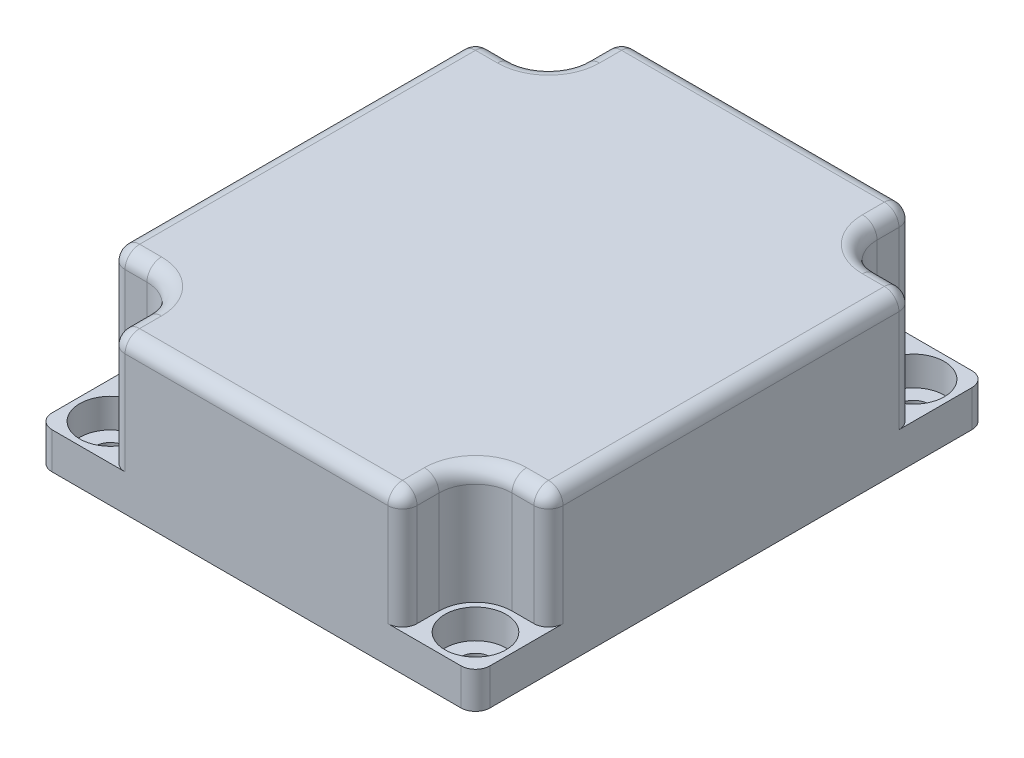
SolidWorks part; units mm, degrees
material "ABS"
ref_plane "正面" through (0, 0, 0) normal (0, 0, 1) x (1, 0, 0)
ref_plane "平面" through (0, 0, 0) normal (0, 1, 0) x (1, 0, 0)
ref_plane "右側面" through (0, 0, 0) normal (1, 0, 0) x (0, 0, -1)
sketch "ｽｹｯﾁ1" plane through (0, 0, 0) normal (0, 1, 0) x (1, 0, 0)
  line L1 (-15, 17.5) -> (15, 17.5)
  line L2 (-15, 17.5) -> (-15, -17.5)
  line L3 (-15, -17.5) -> (15, -17.5)
  line L4 (15, 17.5) -> (15, -17.5)
  line L5 (-15, 17.5) -> (15, -17.5) construction
  line L6 (-15, -17.5) -> (15, 17.5) construction
  point P0 (0, 0)
  dimension "D1" = 30
  dimension "D2" = 35
extrude "ﾎﾞｽ - 押し出し1" add sketch "ｽｹｯﾁ1" along normal blind 10.5
sketch "ｽｹｯﾁ2" plane through (0, 10.5, 0) normal (0, 1, 0) x (1, 0, 0)
  line L0 (15, -17.5) -> (15, 17.5) construction
  line L1 (15, 17.5) -> (-15, 17.5) construction
  line L2 (-15, -17.5) -> (15, -17.5) construction
  line L3 (15, 12.5) -> (15, -12.5)
  line L4 (12.5, 17.5) -> (17, 17.5)
  line L5 (17, 17.5) -> (17, -17.5)
  line L6 (17, -17.5) -> (12.5, -17.5)
  line L7 (10, 15) -> (10, 17.5)
  line L8 (10, 17.5) -> (12.5, 17.5)
  line L9 (12.5, 12.5) -> (15, 12.5)
  line L10 (10, -15) -> (10, -17.5)
  line L11 (10, -17.5) -> (12.5, -17.5)
  line L12 (12.5, -12.5) -> (15, -12.5)
  arc A0 (10, 15) -> (12.5, 12.5) centre (12.5, 15) ccw
  arc A1 (12.5, -12.5) -> (10, -15) centre (12.5, -15) ccw
  dimension "D1" = 5
  dimension "D2" = 5
  dimension "D3" = 2
extrude "ｶｯﾄ - 押し出し1" cut sketch "ｽｹｯﾁ2" against normal blind 8
mirror "ﾐﾗｰ1" about plane through (0, 0, 0) normal (1, 0, 0) of "ｶｯﾄ - 押し出し1"
fillet "ﾌｨﾚｯﾄ1" radius 1 28 edges at (-13.75, 10.5, -12.5) (-10.7322, 10.5, -13.2322) (-10, 10.5, -16.25) (0, 10.5, -17.5) (10, 10.5, -16.25) (10.7322, 10.5, -13.2322) (13.75, 10.5, -12.5) (15, 10.5, 0) (13.75, 10.5, 12.5) (10.7322, 10.5, 13.2322) (10, 10.5, 16.25) (0, 10.5, 17.5) (-10, 10.5, 16.25) (-10.7322, 10.5, 13.2322) (-13.75, 10.5, 12.5) (-15, 10.5, 0) (-15, 6.5, -12.5) (-10, 6.5, -17.5) (-15, 1.25, -17.5) (15, 1.25, -17.5) (15, 6.5, -12.5) (10, 6.5, -17.5) (15, 1.25, 17.5) (-15, 1.25, 17.5) (15, 6.5, 12.5) (10, 6.5, 17.5) (-10, 6.5, 17.5) (-15, 6.5, 12.5)
hole_wizard "M2 なべ頭ねじ用座ぐり穴1" positions "ｽｹｯﾁ3" profile "ｽｹｯﾁ4" counterbore size "M2" standard "ISO"
sketch "ｽｹｯﾁ3" plane through (0, 2.5, 0) normal (0, 1, 0) x (1, 0, 0)
  point P0 (12.5, -15)
  point P3 (12.5, 15)
  point P6 (-12.5, 15)
  point P9 (-12.5, -15)
sketch "ｽｹｯﾁ4" plane through (12.5, 2.5, 15) normal (1, 0, 0) x (0, 0, 1)
  line L0 (0, 0) -> (0, 20.6309)
  line L1 (0, 20.6309) -> (1.05, 20)
  line L2 (1.05, 20) -> (1.05, 2)
  line L3 (1.05, 2) -> (2.1, 2)
  line L4 (2.1, 2) -> (2.1, 0)
  line L5 (2.1, 0) -> (0, 0)
  line L10 (0, 20.6309) -> (-1.05, 20) construction
  line L11 (0, -6.35) -> (0, 107.95) construction
  dimension "穴の直径" = 2.1
  dimension "穴の深さ" = 20
  dimension "座ぐり穴の直径" = 4.2
  dimension "座ぐり穴の深さ" = 2
  dimension "ﾄﾞﾘﾙ角度" = 118
